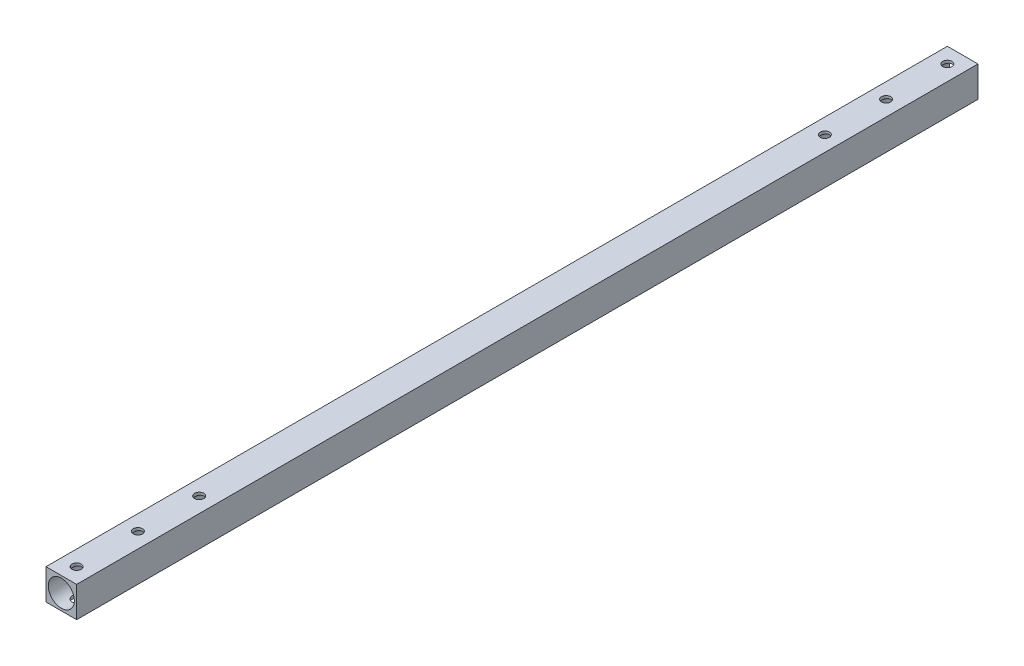
SolidWorks part; units mm, degrees
material "Thornel VCB-20 Carbon Cloth"
ref_plane "Front Plane" through (0, 0, 0) normal (0, 0, 1) x (1, 0, 0)
ref_plane "Top Plane" through (0, 0, 0) normal (0, 1, 0) x (1, 0, 0)
ref_plane "Right Plane" through (0, 0, 0) normal (1, 0, 0) x (0, 0, -1)
sketch "Sketch1" plane through (0, 0, 0) normal (0, 0, 1) x (1, 0, 0)
  line L1 (-5, -5) -> (5, -5)
  line L2 (-5, -5) -> (-5, 5)
  line L3 (-5, 5) -> (5, 5)
  line L4 (5, -5) -> (5, 5)
  line L5 (-5, -5) -> (5, 5) construction
  line L6 (-5, 5) -> (5, -5) construction
  circle A0 centre (0, 0) radius 4.25
  point P0 (0, 0)
  dimension "D3" = 8.5
  dimension "D1" = 10
  dimension "D2" = 10
extrude "Boss-Extrude1" add sketch "Sketch1" along normal blind 294.2
sketch "Sketch2" plane through (0, 5, 0) normal (0, 1, 0) x (1, 0, 0)
  line L0 (0, 0) -> (0, -5) construction
  line L1 (5, 0) -> (-5, 0) construction
  line L2 (0, -5) -> (0, -25) construction
  line L3 (0, -25) -> (0, -45) construction
  line L4 (0, -294.2) -> (0, -289.2) construction
  line L5 (5, -294.2) -> (-5, -294.2) construction
  line L6 (0, -289.2) -> (0, -269.2) construction
  line L7 (0, -269.2) -> (0, -249.2) construction
  circle A0 centre (0, -5) radius 1.5
  circle A1 centre (0, -25) radius 1.5
  circle A2 centre (0, -45) radius 1.5
  circle A3 centre (0, -289.2) radius 1.5
  circle A4 centre (0, -269.2) radius 1.5
  circle A5 centre (0, -249.2) radius 1.5
  dimension "D3" = 3
  dimension "D6" = 3
  dimension "D1" = 20
  dimension "D2" = 5
  dimension "D4" = 20
  dimension "D5" = 5
extrude "Cut-Extrude1" cut sketch "Sketch2" against normal through all
